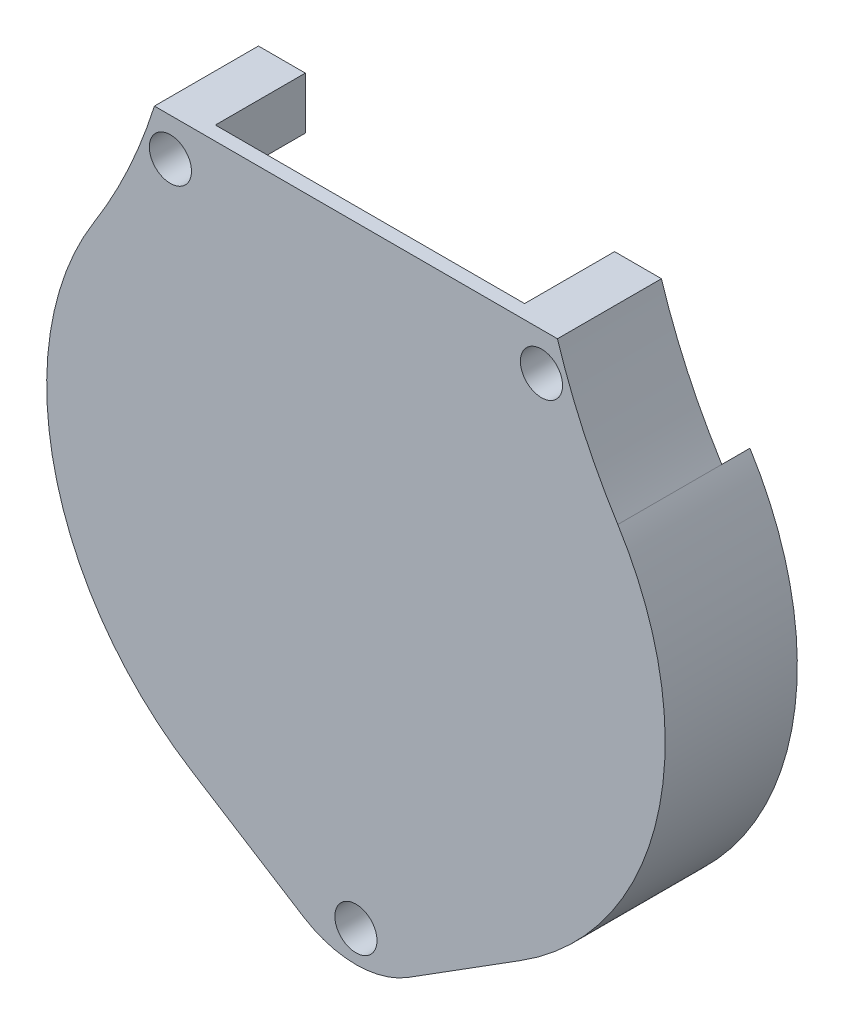
SolidWorks part; units mm, degrees
ref_plane "Front Plane" through (0, 0, 0) normal (0, 0, 1) x (1, 0, 0)
ref_plane "Top Plane" through (0, 0, 0) normal (0, 1, 0) x (1, 0, 0)
ref_plane "Right Plane" through (0, 0, 0) normal (1, 0, 0) x (0, 0, -1)
sketch "Sketch1" plane through (0, 0, 0) normal (0, 0, 1) x (1, 0, 0)
  line L0 (0, 0) -> (0, 110.5744) construction
  line L1 (-15.875, 107.638) -> (-15.875, 41.8859) construction
  line L2 (15.875, 105.2522) -> (15.875, 41.8859) construction
  line L3 (-33.1911, -33.02) -> (48.9076, -33.02) construction
  line L4 (0, 0) -> (0, -55.6039) construction
  line L5 (-4.7378, -30.0359) -> (-14.8903, -23.6415)
  line L6 (4.7378, -30.0359) -> (14.8903, -23.6415)
  line L7 (-46.7853, 13.97) -> (63.7962, 13.97) construction
  line L8 (-37.5439, 26.67) -> (33.7617, 26.67) construction
  line L15 (-18.2073, 26.67) -> (18.2073, 26.67)
  arc A0 (-23.6589, 14.8628) -> (-14.8903, -23.6415) centre (0, 0) ccw
  arc A1 (4.7378, -30.0359) -> (-4.7378, -30.0359) centre (0, -22.5136) cw
  arc A2 (-18.2073, 26.67) -> (-23.6589, 14.8628) centre (-66.675, 41.8859) cw
  arc A3 (18.2073, 26.67) -> (23.6589, 14.8628) centre (66.675, 41.8859) ccw
  arc A4 (23.6589, 14.8628) -> (14.8903, -23.6415) centre (0, 0) cw
  point P15 (0, -33.02)
  dimension "D1" = 31.75
  dimension "D3" = 55.88
  dimension "D5" = 8.89
  dimension "D8" = 50.8
  dimension "D4" = 33.02
  dimension "D6" = 13.97
  dimension "D7" = 12.7
extrude "Boss-Extrude1" add sketch "Sketch1" along normal blind 11.938
sketch "Sketch2" plane through (0, 0, 0) normal (0, 0, -1) x (-1, 0, 0)
  line L0 (-11.7336, 23.241) -> (11.7336, 23.241)
  line L1 (-18.2073, 26.67) -> (18.2073, 26.67) construction
  arc A0 (-11.7336, 23.241) -> (11.7336, 23.241) centre (0, 0) ccw
  point P7 (-38.7475, 23.241)
  point P8 (38.1276, 23.241)
  dimension "D1" = 3.429
extrude "Cut-Extrude1" cut sketch "Sketch2" against normal blind 11.43
sketch "Sketch3" plane through (0, 0, 0) normal (0, 0, -1) x (-1, 0, 0)
  line L0 (0, 0) -> (0, 57.7751) construction
  line L2 (-13.97, 37.2037) -> (13.97, 37.2037)
  line L3 (-13.97, 37.2037) -> (-13.97, 11.3578)
  line L4 (-13.97, 11.3578) -> (13.97, 11.3578)
  line L5 (13.97, 37.2037) -> (13.97, 11.3578)
  dimension "D1" = 13.97
  dimension "D2" = 27.94
extrude "Cut-Extrude2" cut sketch "Sketch3" against normal blind 10.668
sketch "Sketch4" plane through (0, 0, 11.938) normal (0, 0, 1) x (1, 0, 0)
  circle A0 centre (0, -28.575) radius 1.905
  circle A1 centre (-16.764, 23.241) radius 1.905
  circle A2 centre (16.764, 23.241) radius 1.905
  point P2 (0, 0)
  dimension "D1" = 28.575
  dimension "D2" = 23.241
  dimension "D3" = 23.241
  dimension "D4" = 16.764
  dimension "D5" = 16.764
extrude "Cut-Extrude3" cut sketch "Sketch4" against normal blind 8.636
sketch "Sketch5" plane through (0, 0, 3.302) normal (0, 0, 1) x (1, 0, 0)
  circle A0 centre (-16.764, 23.241) radius 1.143
  circle A1 centre (16.764, 23.241) radius 1.143
  circle A2 centre (0, -28.575) radius 1.143
extrude "Cut-Extrude4" cut sketch "Sketch5" against normal blind 21.59
sketch "Sketch6" plane through (0, 0, 0) normal (0, 0, -1) x (-1, 0, 0)
  line L0 (-18.354, -33.02) -> (21.767, -33.02) construction
  line L1 (0, 0) -> (0, -48.2332) construction
  line L2 (-4.7378, -30.0359) -> (-14.8903, -23.6415) construction
  line L3 (4.7378, -30.0359) -> (14.8903, -23.6415) construction
  line L4 (-15.875, 76.6342) -> (-15.875, 41.8859) construction
  line L5 (15.875, 75.3139) -> (15.875, 41.8859) construction
  line L6 (-23.6589, 14.8628) -> (-4.7378, -30.0359)
  line L7 (23.6589, 14.8628) -> (4.7378, -30.0359)
  line L8 (-18.2073, 26.67) -> (18.2073, 26.67)
  arc A0 (-23.6589, 14.8628) -> (-14.8903, -23.6415) centre (0, 0) ccw construction
  arc A1 (-18.2073, 26.67) -> (-23.6589, 14.8628) centre (-66.675, 41.8859) cw
  arc A2 (23.6589, 14.8628) -> (14.8903, -23.6415) centre (0, 0) cw construction
  arc A3 (18.2073, 26.67) -> (23.6589, 14.8628) centre (66.675, 41.8859) ccw
  arc A4 (4.7378, -30.0359) -> (-4.7378, -30.0359) centre (0, -22.5136) cw
  point P19 (0, -33.02)
  point P25 (-33.7669, 34.8753)
  dimension "D2" = 55.88
  dimension "D5" = 50.8
  dimension "D6" = 8.89
  dimension "D1" = 33.02
  dimension "D3" = 31.75
  dimension "D4" = 15.875
extrude "Cut-Extrude5" cut sketch "Sketch6" against normal blind 2.54
